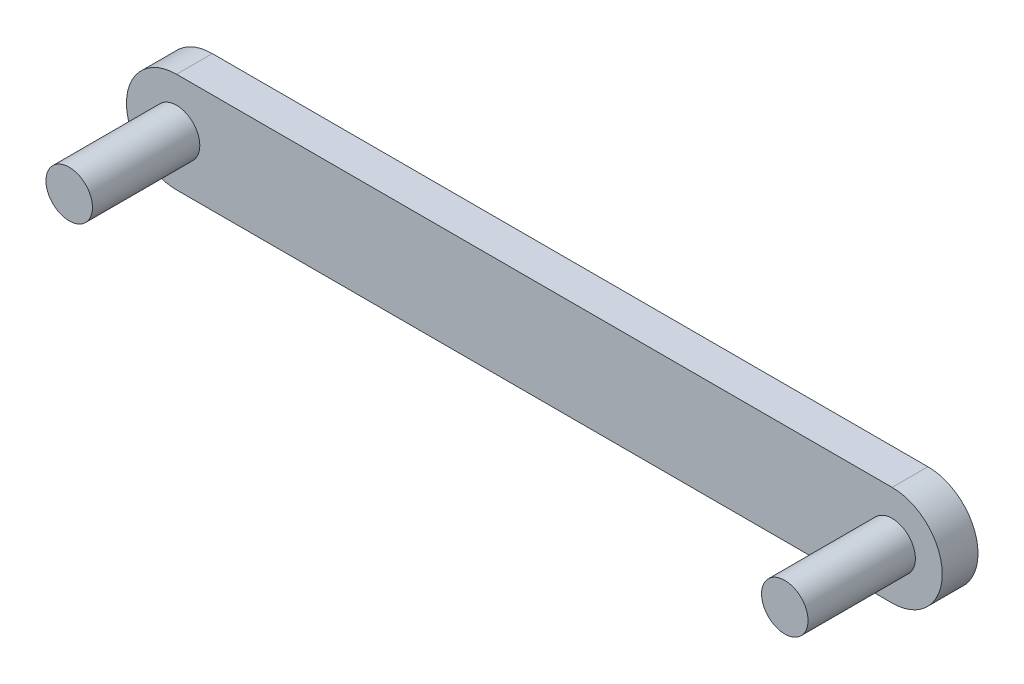
SolidWorks part; units mm, degrees
ref_plane "Front Plane" through (0, 0, 0) normal (0, 0, 1) x (1, 0, 0)
ref_plane "Top Plane" through (0, 0, 0) normal (0, 1, 0) x (1, 0, 0)
ref_plane "Right Plane" through (0, 0, 0) normal (1, 0, 0) x (0, 0, -1)
sketch "Sketch1" plane through (0, 0, 0) normal (0, 0, 1) x (1, 0, 0)
  line L0 (100, 0) -> (-100, 0) construction
  line L1 (100, -14) -> (-100, -14)
  line L2 (100, 14) -> (-100, 14)
  arc A0 (100, -14) -> (100, 14) centre (100, 0) ccw
  arc A1 (-100, 14) -> (-100, -14) centre (-100, 0) ccw
  point P3 (0, 0)
  dimension "D2" = 14
  dimension "D1" = 200
extrude "Boss-Extrude1" add sketch "Sketch1" along normal blind 10
sketch "Sketch2" plane through (0, 0, 10) normal (0, 0, 1) x (1, 0, 0)
  circle A0 centre (100, 0) radius 6.5
  circle A1 centre (-100, 0) radius 6.5
  arc A2 (100, -14) -> (100, 14) centre (100, 0) ccw construction
  arc A3 (-100, 14) -> (-100, -14) centre (-100, 0) ccw construction
  dimension "D1" = 13
extrude "Boss-Extrude2" add sketch "Sketch2" along normal blind 30
